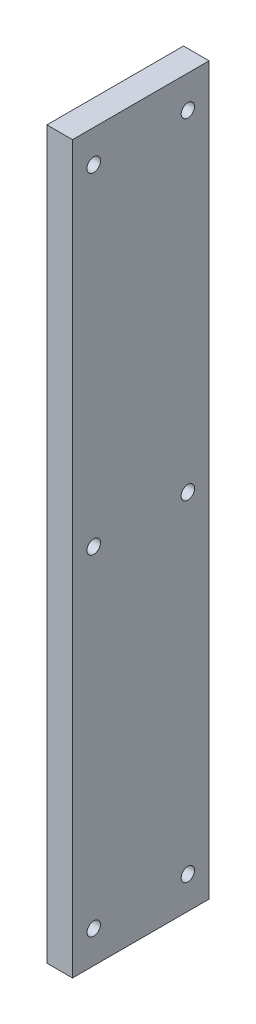
SolidWorks part; units mm, degrees
ref_plane "Alzado" through (0, 0, 0) normal (0, 0, 1) x (1, 0, 0)
ref_plane "Planta" through (0, 0, 0) normal (0, 1, 0) x (1, 0, 0)
ref_plane "Vista lateral" through (0, 0, 0) normal (1, 0, 0) x (0, 0, -1)
sketch "Croquis1" plane through (0, 0, 0) normal (1, 0, 0) x (0, 0, -1)
  line L1 (25.4, -135) -> (-25.4, -135)
  line L2 (25.4, -135) -> (25.4, 135)
  line L3 (25.4, 135) -> (-25.4, 135)
  line L4 (-25.4, -135) -> (-25.4, 135)
  line L5 (25.4, -135) -> (-25.4, 135) construction
  line L6 (25.4, 135) -> (-25.4, -135) construction
  point P0 (0, 0)
  dimension "D1" = 50.8
  dimension "D2" = 270
extrude "Saliente-Extruir1" add sketch "Croquis1" along normal blind 9.525
sketch "Croquis2" plane through (9.525, 0, 0) normal (1, 0, 0) x (0, 0, -1)
  line L0 (-25.4, -135) -> (25.4, -135) construction
  line L1 (-17.5, 123) -> (17.5, 123) construction
  line L2 (-17.5, 123) -> (-17.5, -123) construction
  line L3 (-17.5, -123) -> (17.5, -123) construction
  line L4 (17.5, 123) -> (17.5, -123) construction
  line L5 (-17.5, 123) -> (17.5, -123) construction
  line L6 (-17.5, -123) -> (17.5, 123) construction
  circle A0 centre (-17.5, -123) radius 2.4849
  circle A1 centre (17.5, -123) radius 2.4862
  circle A2 centre (17.5, 123) radius 2.4808
  circle A3 centre (-17.5, 123) radius 2.5336
  circle A4 centre (-17.5, 0) radius 2.5151
  circle A5 centre (17.5, 0) radius 2.508
  point P0 (0, 0)
  dimension "D1" = 12
  dimension "D2" = 35
extrude "Cortar-Extruir1" cut sketch "Croquis2" against normal blind 9.525
